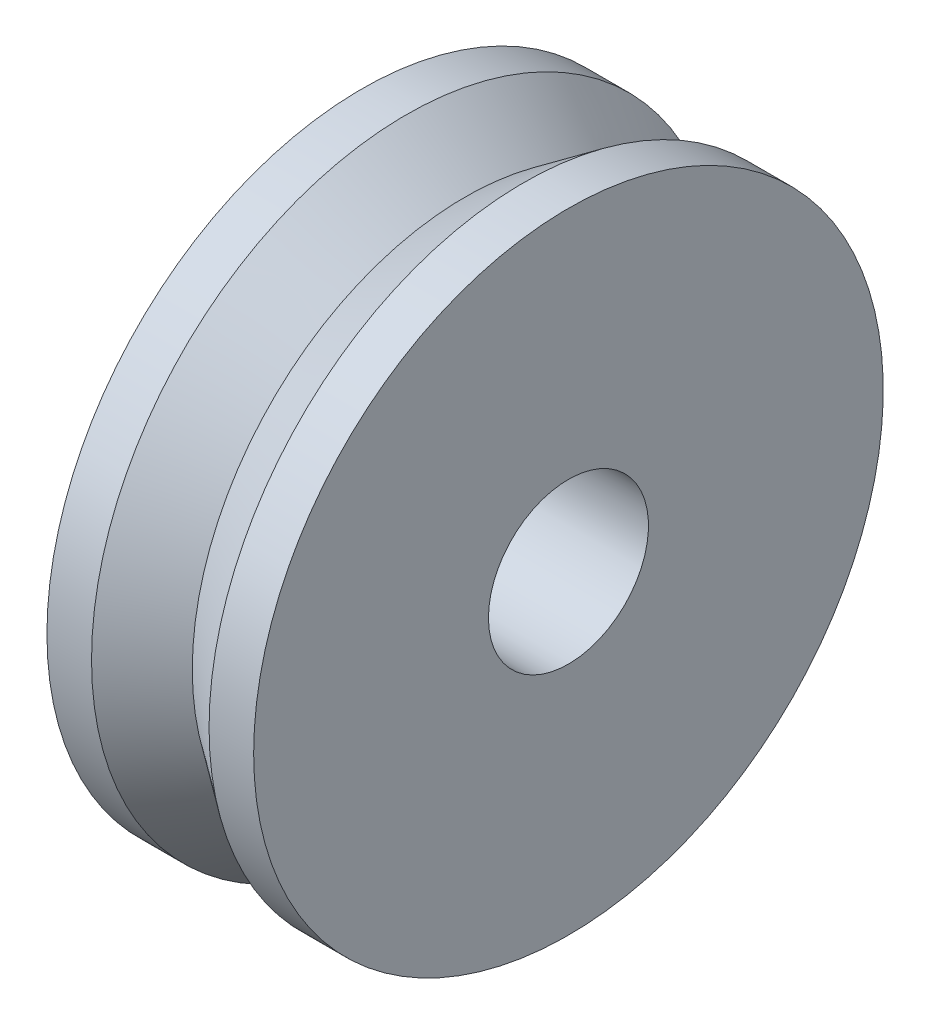
SolidWorks part; units mm, degrees
ref_plane "Front Plane" through (0, 0, 0) normal (0, 0, 1) x (1, 0, 0)
ref_plane "Top Plane" through (0, 0, 0) normal (0, 1, 0) x (1, 0, 0)
ref_plane "Right Plane" through (0, 0, 0) normal (1, 0, 0) x (0, 0, -1)
sketch "Sketch1" plane through (0, 0, 0) normal (0, 0, 1) x (1, 0, 0)
  line L0 (-1.6876, 2.8648) -> (2.2524, 2.8648) construction
  line L1 (-1.6876, 2.8648) -> (-0.8376, 2.8648)
  line L2 (-0.8376, 2.8648) -> (0.2824, 2.0648)
  line L3 (0.2824, 2.0648) -> (1.4024, 2.8648)
  line L4 (1.4024, 2.8648) -> (2.2524, 2.8648)
  line L5 (0.2824, 2.8648) -> (0.2824, 0.6888) construction
  line L6 (-1.6876, 2.8648) -> (-1.6876, -3.1352)
  line L7 (-1.6876, -3.1352) -> (2.2524, -3.1352)
  line L8 (2.2524, -3.1352) -> (2.2524, 2.8648)
  dimension "D1" = 3.94
  dimension "D2" = 0.85
  dimension "D3" = 0.85
  dimension "D4" = 0.8
  dimension "D5" = 6
revolve "Revolve1" add sketch "Sketch1" angle 360 about L7
sketch "Sketch2" plane through (-1.6876, 0, 0) normal (-1, 0, 0) x (0, 0, 1)
  circle A0 centre (0, -3.1352) radius 1.525
  dimension "D1" = 3.05
extrude "Cut-Extrude1" cut sketch "Sketch2" against normal through all
